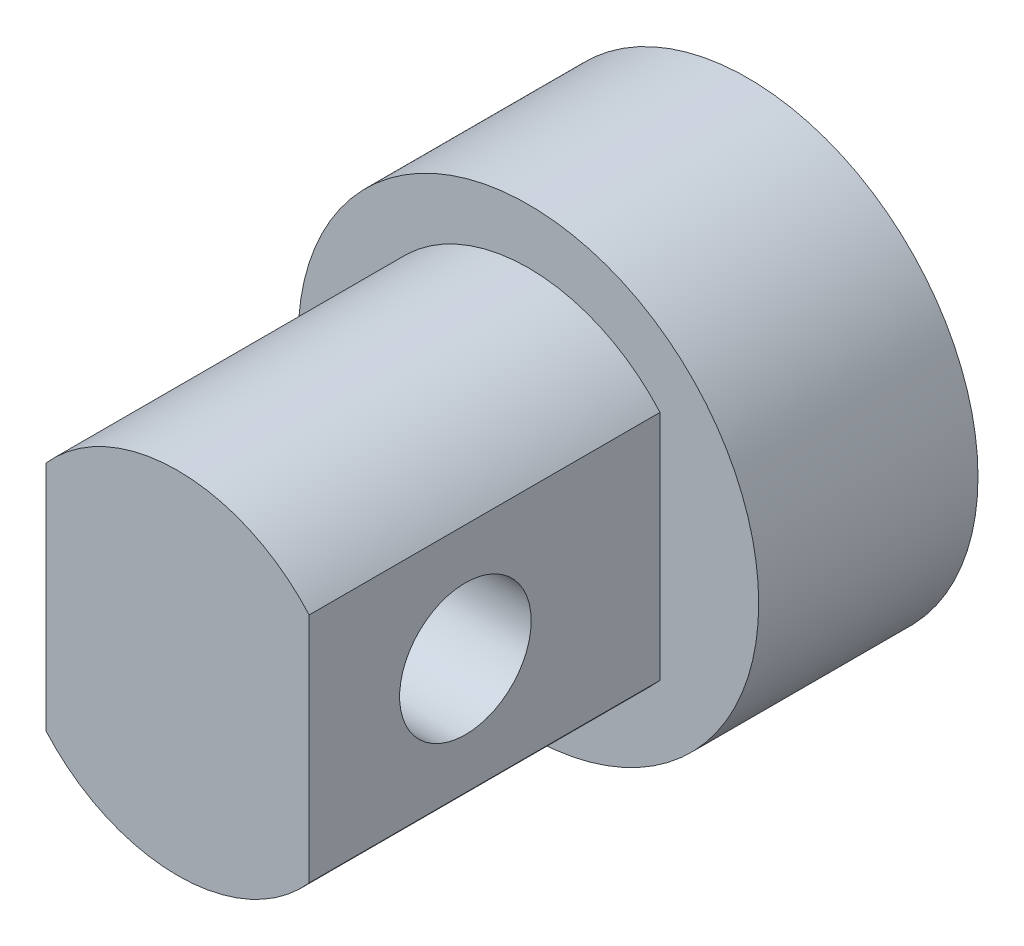
SolidWorks part; units mm, degrees
ref_plane "Front Plane" through (0, 0, 0) normal (0, 0, 1) x (1, 0, 0)
ref_plane "Top Plane" through (0, 0, 0) normal (0, 1, 0) x (1, 0, 0)
ref_plane "Right Plane" through (0, 0, 0) normal (1, 0, 0) x (0, 0, -1)
sketch "Sketch1" plane through (0, 0, 0) normal (0, 0, 1) x (1, 0, 0)
  line L2 (-6, 5.2915) -> (-6, -5.2915)
  line L4 (6, 5.2915) -> (6, -5.2915)
  arc A0 (-6, -5.2915) -> (6, -5.2915) centre (0, 0) ccw
  arc A1 (6, 5.2915) -> (-6, 5.2915) centre (0, 0) ccw
extrude "Boss-Extrude1" add sketch "Sketch1" along normal blind 16
sketch "Sketch2" plane through (0, 0, 0) normal (0, 0, 1) x (1, 0, 0)
  circle A0 centre (0, 0) radius 10.5
extrude "Boss-Extrude2" add sketch "Sketch2" against normal blind 10
sketch "Sketch3" plane through (0, 0, 0) normal (1, 0, 0) x (0, 0, -1)
  line L0 (-23.9207, 0) -> (20.4285, 0) construction
  line L1 (-15.8755, -11.8995) -> (-15.8755, 11.9006) construction
  circle A0 centre (-8.8755, 0) radius 3
  dimension "D1" = 7
extrude "Cut-Extrude1" cut sketch "Sketch3" against normal through all both and the other way through all
